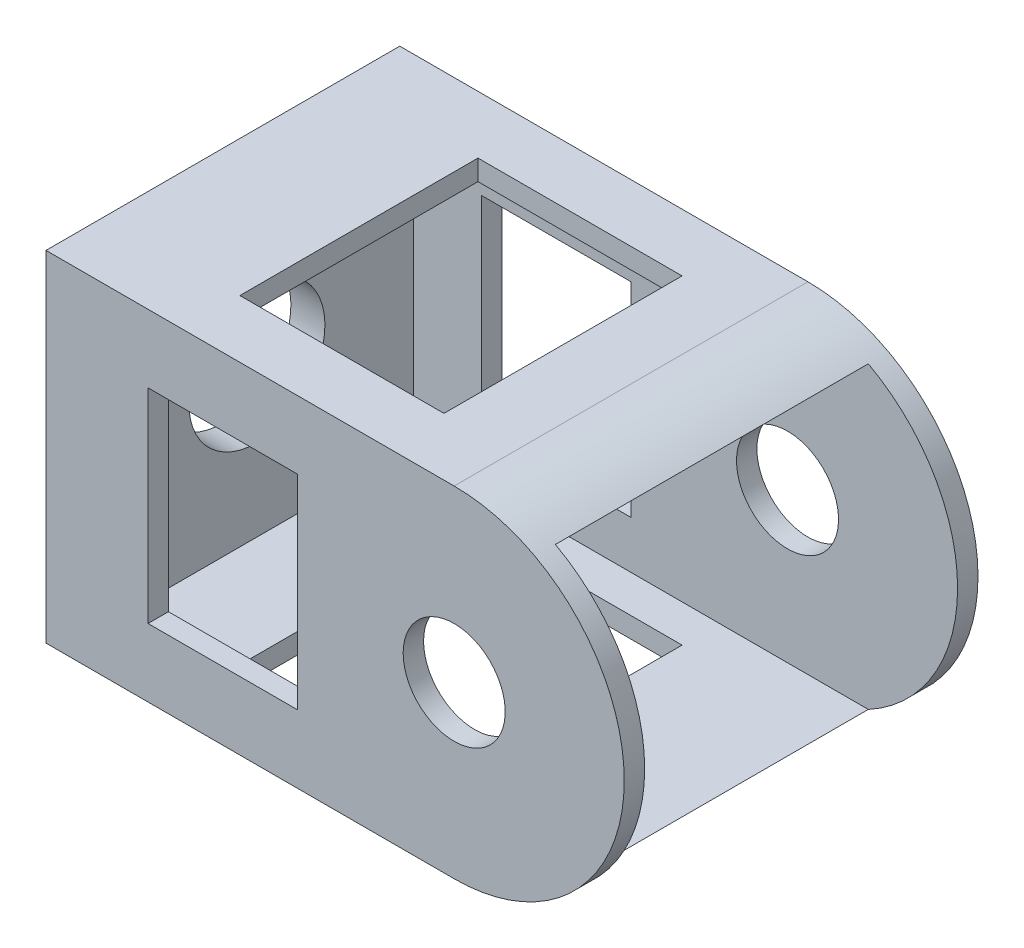
SolidWorks part; units mm, degrees
ref_plane "正面" through (0, 0, 0) normal (0, 0, 1) x (1, 0, 0)
ref_plane "平面" through (0, 0, 0) normal (0, 1, 0) x (1, 0, 0)
ref_plane "右側面" through (0, 0, 0) normal (1, 0, 0) x (0, 0, -1)
sketch "ｽｹｯﾁ1" plane through (0, 0, 0) normal (0, 0, 1) x (1, 0, 0)
  line L0 (0, -25) -> (55, -25) construction
  line L1 (0, 0) -> (55, 0)
  line L2 (0, 0) -> (0, -50)
  line L3 (0, -50) -> (55, -50)
  line L4 (55, 0) -> (55, -50) construction
  line L5 (10, -10) -> (32, -10)
  line L6 (10, -10) -> (10, -40)
  line L7 (10, -40) -> (32, -40)
  line L8 (32, -10) -> (32, -40)
  arc A0 (55, -50) -> (55, 0) centre (55, -25) ccw
  circle A1 centre (55, -25) radius 7.5
  dimension "D6" = 15
  dimension "D1" = 55
  dimension "D2" = 50
  dimension "D3" = 30
  dimension "D4" = 22
  dimension "D5" = 10
extrude "ﾎﾞｽ - 押し出し1" add sketch "ｽｹｯﾁ1" along normal blind 52
sketch "ｽｹｯﾁ2" plane through (0, 0, 0) normal (0, 1, 0) x (1, 0, 0)
  line L0 (0, -26) -> (47.4636, -26) construction
  line L1 (15, -8.5) -> (45, -8.5)
  line L2 (15, -8.5) -> (15, -43.5)
  line L3 (15, -43.5) -> (45, -43.5)
  line L4 (45, -8.5) -> (45, -43.5)
  line L5 (0, -52) -> (0, 0) construction
  point P8 (0, 0)
  dimension "D1" = 35
  dimension "D2" = 30
  dimension "D3" = 15
extrude "ｶｯﾄ - 押し出し1" cut sketch "ｽｹｯﾁ2" against normal through all
sketch "ｽｹｯﾁ3" plane through (0, 0, 0) normal (-1, 0, 0) x (0, 0, 1)
  line L5 (0, 0) -> (52, 0) construction
  line L6 (0, 0) -> (0, -50) construction
  line L7 (0, -50) -> (52, -50) construction
  line L8 (52, 0) -> (52, -50) construction
  line L20 (3, -3) -> (3, -47)
  line L21 (3, -47) -> (49, -47)
  line L22 (49, -47) -> (49, -3)
  line L23 (49, -3) -> (3, -3)
  line L24 (3, -3) -> (3, -47)
  line L25 (3, -47) -> (49, -47)
  line L26 (49, -47) -> (49, -3)
  line L27 (49, -3) -> (3, -3)
  dimension "D1" = 3
extrude "ｶｯﾄ - 押し出し2" cut sketch "ｽｹｯﾁ3" against normal through all
sketch "ｽｹｯﾁ4" plane through (0, 0, 0) normal (-1, 0, 0) x (0, 0, 1)
  line L1 (0, 0) -> (52, 0)
  line L2 (0, 0) -> (0, -50)
  line L3 (0, -50) -> (52, -50)
  line L4 (52, 0) -> (52, -50)
extrude "ﾎﾞｽ - 押し出し2" add sketch "ｽｹｯﾁ4" along normal blind 5
sketch "ｽｹｯﾁ5" plane through (-5, 0, 0) normal (-1, 0, 0) x (0, 0, 1)
  line L0 (52, -25) -> (0, -25) construction
  line L1 (52, -50) -> (52, 0) construction
  line L2 (0, 0) -> (0, -50) construction
  circle A0 centre (26, -25) radius 10
  dimension "D1" = 20
extrude "ｶｯﾄ - 押し出し3" cut sketch "ｽｹｯﾁ5" against normal through all
